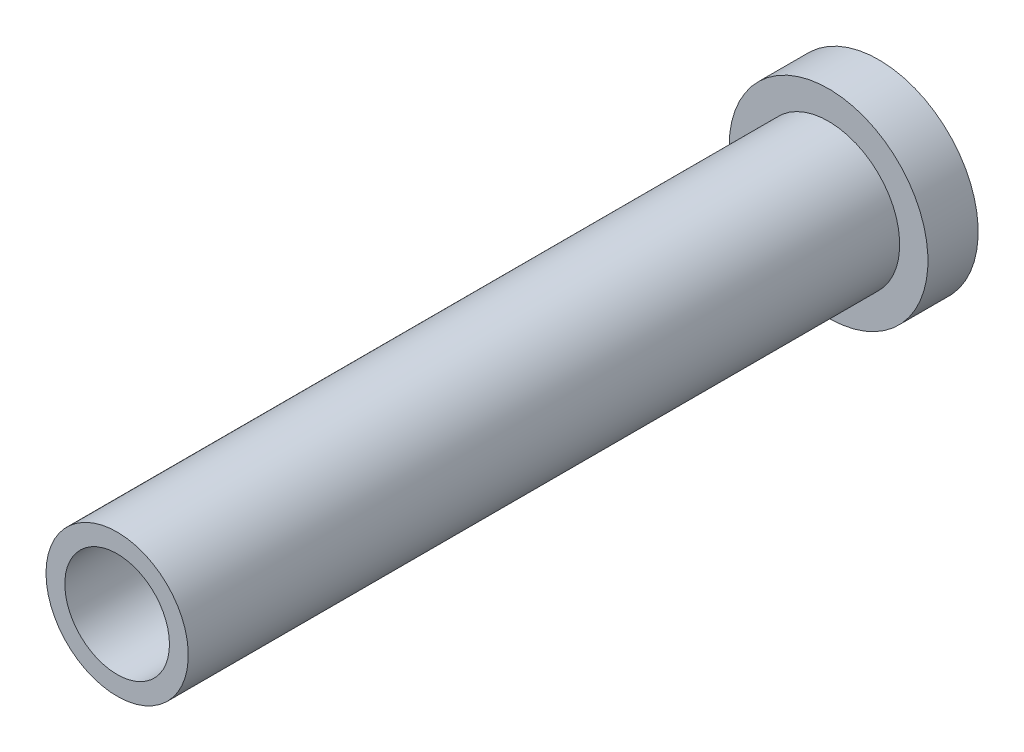
SolidWorks part; units mm, degrees
ref_plane "前视基准面" through (0, 0, 0) normal (0, 0, 1) x (1, 0, 0)
ref_plane "上视基准面" through (0, 0, 0) normal (0, 1, 0) x (1, 0, 0)
ref_plane "右视基准面" through (0, 0, 0) normal (1, 0, 0) x (0, 0, -1)
sketch "草图1" plane through (0, 0, 0) normal (0, 0, 1) x (1, 0, 0)
  circle A0 centre (0, 0) radius 4.75
  dimension "D1" = 9.5
extrude "凸台-拉伸1" add sketch "草图1" along normal blind 2.4
sketch "草图2" plane through (0, 0, 2.4) normal (0, 0, 1) x (1, 0, 0)
  circle A0 centre (0, 0) radius 3.4
  dimension "D1" = 6.8
extrude "凸台-拉伸2" add sketch "草图2" along normal blind 34
sketch "草图3" plane through (0, 0, 36.4) normal (0, 0, 1) x (1, 0, 0)
  circle A0 centre (0, 0) radius 2.5
  dimension "D1" = 5
extrude "切除-拉伸1" cut sketch "草图3" against normal blind 5.4
